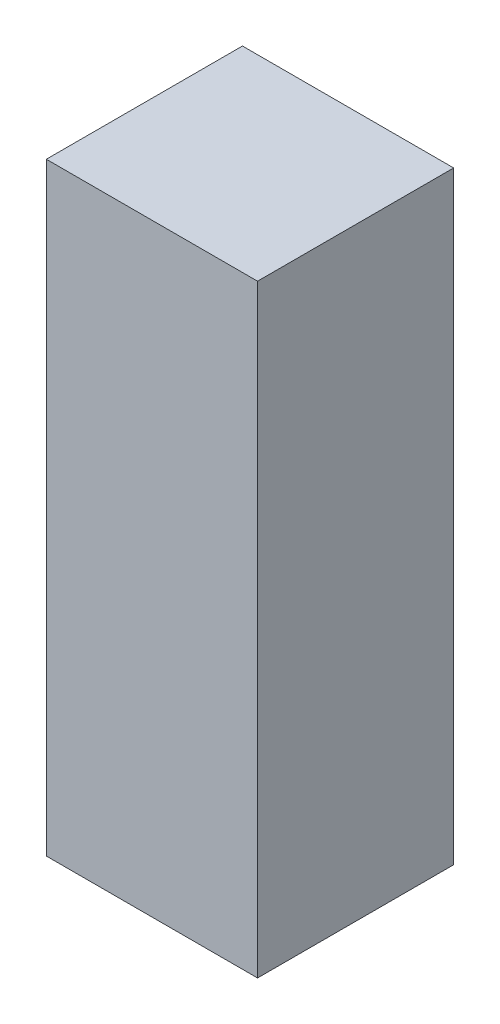
SolidWorks part; units mm, degrees
ref_plane "Front Plane" through (0, 0, 0) normal (0, 0, 1) x (1, 0, 0)
ref_plane "Top Plane" through (0, 0, 0) normal (0, 1, 0) x (1, 0, 0)
ref_plane "Right Plane" through (0, 0, 0) normal (1, 0, 0) x (0, 0, -1)
other "Configuration Table"
sketch "Sketch1" plane through (0, 0, 0) normal (0, 0, 1) x (1, 0, 0)
  line L1 (24, 860) -> (38, 860)
  line L2 (24, 860) -> (24, 900)
  line L3 (24, 900) -> (38, 900)
  line L4 (38, 860) -> (38, 900)
extrude "OVEN_yag_kabi_kapagi_mentese_1_1" add sketch "Sketch1" along normal blind 13 from offset 20 separate body
